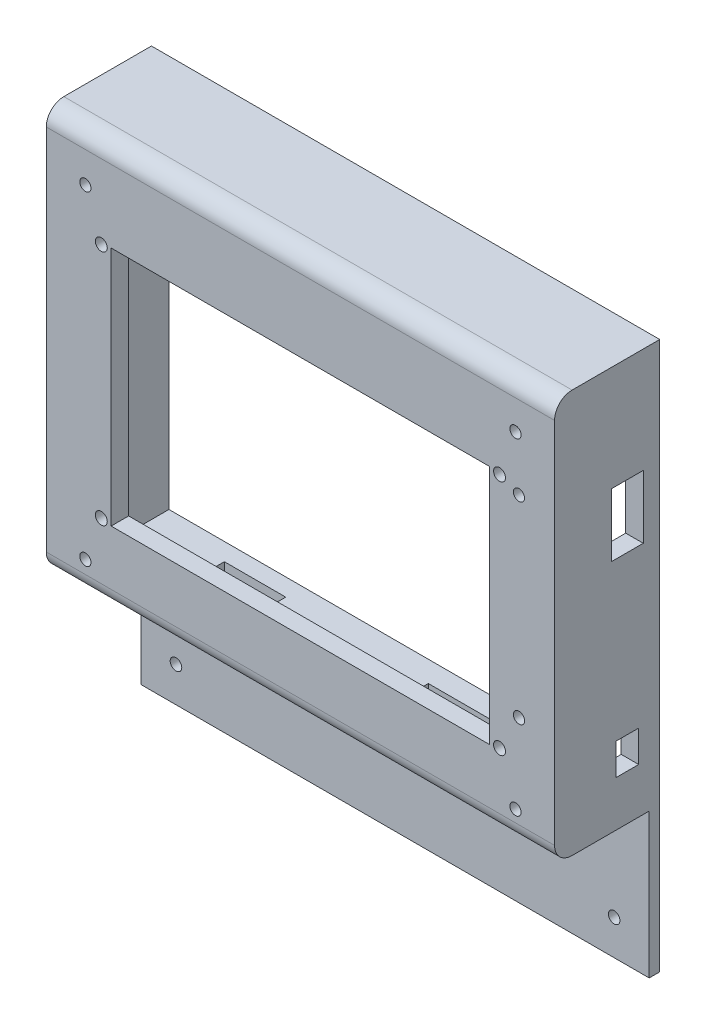
SolidWorks part; units mm, degrees
ref_plane "前视基准面" through (0, 0, 0) normal (0, 0, 1) x (1, 0, 0)
ref_plane "上视基准面" through (0, 0, 0) normal (0, 1, 0) x (1, 0, 0)
ref_plane "右视基准面" through (0, 0, 0) normal (1, 0, 0) x (0, 0, -1)
sketch "草图1" plane through (0, 0, 0) normal (0, 0, 1) x (1, 0, 0)
  line L0 (-86.7958, 0) -> (86.7958, 0) construction
  line L5 (-49.95, 40.9223) -> (-49.95, -27.6039) construction
  line L6 (-71.9776, 4) -> (71.9776, 4) construction
  line L7 (-61.6077, -23.5) -> (84.4481, -23.5) construction
  line L8 (62.35, 40.9223) -> (62.35, -37.6039) construction
  line L9 (-74.058, 31.5) -> (80.4255, 31.5) construction
  line L10 (-61.35, 65.8418) -> (-61.35, -76.2872) construction
  line L11 (-72.5, 60) -> (72.5, 60)
  line L12 (-72.5, 60) -> (-72.5, -60)
  line L13 (-72.5, -60) -> (72.5, -60)
  line L14 (72.5, 60) -> (72.5, -60)
  line L15 (-72.5, 60) -> (72.5, -60) construction
  line L16 (-72.5, -60) -> (72.5, 60) construction
  line L17 (61.35, 54.8887) -> (61.35, -55.3109) construction
  circle A0 centre (-61.35, 46.25) radius 1.6
  circle A1 centre (61.35, -46.6) radius 1.6
  circle A2 centre (61.35, 46.6) radius 1.6
  circle A3 centre (-61.35, -46.25) radius 1.6
  circle A4 centre (62.35, 31.5) radius 1.6
  circle A5 centre (62.35, -23.5) radius 1.6
  circle A6 centre (62.35, 31.5) radius 1.6
  circle A7 centre (62.35, -23.5) radius 1.6
  circle A8 centre (-49.95, 31.5) radius 1.6
  circle A9 centre (-49.95, 31.5) radius 1.6
  circle A10 centre (-49.95, -23.5) radius 1.6
  point P0 (0, 0)
  point P5 (0, 0)
  dimension "D1" = 3.2
  dimension "D2" = 3.2
  dimension "D3" = 3.2
  dimension "D6" = 3.2
  dimension "D7" = 3.2
  dimension "D12" = 3.2
  dimension "D17" = 61.35
  dimension "D18" = 1
  dimension "D19" = 3.2
  dimension "D20" = 3.2
  dimension "D21" = 61.35
  dimension "D4" = 27.5
  dimension "D5" = 27.5
  dimension "D8" = 46.25
  dimension "D9" = 46.25
  dimension "D10" = 46.6
  dimension "D11" = 46.6
  dimension "D13" = 15.1
  dimension "D14" = 112.3
  dimension "D15" = 145
  dimension "D16" = 120
extrude "凸台-拉伸1" add sketch "草图1" along normal blind 5 contours L14 L11 L12 L13 A10 A8 A0 A1 A2 A3 A4 A5
sketch "草图2" plane through (0, 0, 5) normal (0, 0, 1) x (1, 0, 0)
  line L0 (-72.5, -55) -> (72.5, -55)
  line L1 (-72.5, 60) -> (-72.5, -60) construction
  line L2 (72.5, 60) -> (72.5, -60) construction
  line L3 (72.5, -55) -> (72.5, -60)
  line L4 (72.5, -60) -> (-72.5, -60)
  line L5 (-72.5, -60) -> (-72.5, -55)
  dimension "D1" = 5
extrude "切除-拉伸1" cut sketch "草图2" against normal blind 8
sketch "草图3" plane through (0, 0, 5) normal (0, 0, 1) x (1, 0, 0)
  line L0 (-67.5, -52) -> (67.5, -52)
  line L1 (67.5, -52) -> (67.5, 55)
  line L2 (67.5, 55) -> (-67.5, 55)
  line L3 (-67.5, 55) -> (-67.5, -52)
  line L4 (-72.5, -55) -> (72.5, -55)
  line L5 (72.5, -55) -> (72.5, 60)
  line L6 (72.5, 60) -> (-72.5, 60)
  line L7 (-72.5, 60) -> (-72.5, -55)
  dimension "D1" = 5
  dimension "D2" = 5
  dimension "D3" = 5
  dimension "D4" = 3
extrude "凸台-拉伸6" add sketch "草图3" against normal blind 30
sketch "草图4" plane through (0, -55, 0) normal (0, -1, 0) x (-1, 0, 0)
  line L0 (72.5, 22) -> (-72.5, 22)
  line L1 (72.5, 25) -> (72.5, -5) construction
  line L2 (-72.5, 25) -> (-72.5, -5) construction
  line L3 (-72.5, 22) -> (-72.5, 25)
  line L4 (-72.5, 25) -> (72.5, 25)
  line L5 (72.5, 25) -> (72.5, 22)
  dimension "D1" = 3
extrude "凸台-拉伸7" add sketch "草图4" along normal blind 41.25
sketch "草图6" plane through (0, -55, 0) normal (0, -1, 0) x (1, 0, 0)
  line L0 (-46.69, -20) -> (-46.69, -3)
  line L1 (72.5, -22) -> (-72.5, -22) construction
  line L2 (-46.69, -3) -> (-29.19, -3)
  line L3 (-29.19, -3) -> (-29.19, -20)
  line L5 (-72.5, -22) -> (-72.5, 5) construction
  line L6 (-46.69, -20) -> (-29.19, -20)
  dimension "D1" = 25.81
  dimension "D2" = 17.5
  dimension "D3" = 2
  dimension "D4" = 17
sketch "草图7" plane through (72.5, 0, 0) normal (1, 0, 0) x (0, 0, -1)
  line L0 (11.3, 12) -> (20.3, 12)
  line L1 (20.3, 12) -> (20.3, 30)
  line L2 (20.3, 30) -> (11.3, 30)
  line L3 (11.3, 30) -> (11.3, 12)
  line L5 (25, -96.25) -> (25, 60) construction
  line L6 (1.449, 21) -> (21.151, 21) construction
  line L8 (-5, 60) -> (25, 60) construction
  point P10 (11.3, 21)
  point P11 (20.3, 21)
  dimension "D1" = 39
  dimension "D2" = 4.7
  dimension "D3" = 9
  dimension "D4" = 18
extrude "切除-拉伸4" cut sketch "草图7" against normal blind 7
sketch "草图8" plane through (0, -55, 0) normal (0, -1, 0) x (1, 0, 0)
  line L3 (42.5, -19) -> (12.5, -19)
  line L6 (12.5, -19) -> (12.5, -13)
  line L7 (12.5, -13) -> (42.5, -13)
  line L8 (42.5, -13) -> (42.5, -19)
  line L9 (72.5, -22) -> (-72.5, -22) construction
  line L10 (72.5, -22) -> (72.5, 5) construction
  dimension "D1" = 3
  dimension "D2" = 6
  dimension "D3" = 30
  dimension "D4" = 30
extrude "切除-拉伸6" cut sketch "草图8" against normal blind 6
sketch "草图9" plane through (72.5, 0, 0) normal (1, 0, 0) x (0, 0, -1)
  line L0 (12.5, -42) -> (19, -42)
  line L1 (19, -42) -> (19, -33)
  line L2 (19, -33) -> (12.5, -33)
  line L3 (12.5, -33) -> (12.5, -42)
  line L4 (22, -96.25) -> (22, -55) construction
  line L5 (22, -55) -> (-5, -55) construction
  dimension "D1" = 3
  dimension "D2" = 13
  dimension "D3" = 9
  dimension "D4" = 6.5
extrude "切除-拉伸7" cut sketch "草图9" against normal blind 6
extrude "切除-拉伸8" cut sketch "草图6" against normal blind 10
sketch "草图11" plane through (0, 0, 5) normal (0, 0, 1) x (1, 0, 0)
  line L0 (-82.7388, 0) -> (94.3727, 0) construction
  line L1 (-54, 34.35) -> (54, 34.35)
  line L2 (-54, 34.35) -> (-54, -34.35)
  line L3 (-54, -34.35) -> (54, -34.35)
  line L4 (54, 34.35) -> (54, -34.35)
  line L5 (-54, 34.35) -> (54, -34.35) construction
  line L6 (-54, -34.35) -> (54, 34.35) construction
  line L7 (0, 77.2917) -> (0, -46.7615) construction
  circle A0 centre (56.8, 33.8) radius 1.7
  circle A2 centre (56.8, -33.8) radius 1.7
  circle A3 centre (-56.8, -33.8) radius 1.7
  circle A4 centre (-56.8, 33.8) radius 1.7
  point P0 (0, 0)
  dimension "D3" = 3.4
  dimension "D4" = 33.8
  dimension "D5" = 56.8
  dimension "D1" = 68.7
  dimension "D2" = 108
extrude "切除-拉伸9" cut sketch "草图11" against normal blind 5
fillet "圆角1" radius 5 1 edges at (0, -55, 5)
fillet "圆角2" radius 5 1 edges at (0, 60, 5)
sketch "草图13" plane through (0, 0, -22) normal (0, 0, 1) x (1, 0, 0)
  line L0 (0, 67.4394) -> (0, -107.3732) construction
  line L1 (72.5, -96.25) -> (-72.5, -96.25) construction
  line L2 (-72.5, -96.25) -> (-72.5, -55) construction
  circle A0 centre (-62.5, -86.25) radius 1.65
  circle A1 centre (62.5, -86.25) radius 1.65
  dimension "D1" = 10
  dimension "D2" = 10
  dimension "D3" = 3.3
extrude "切除-拉伸10" cut sketch "草图13" against normal blind 8
